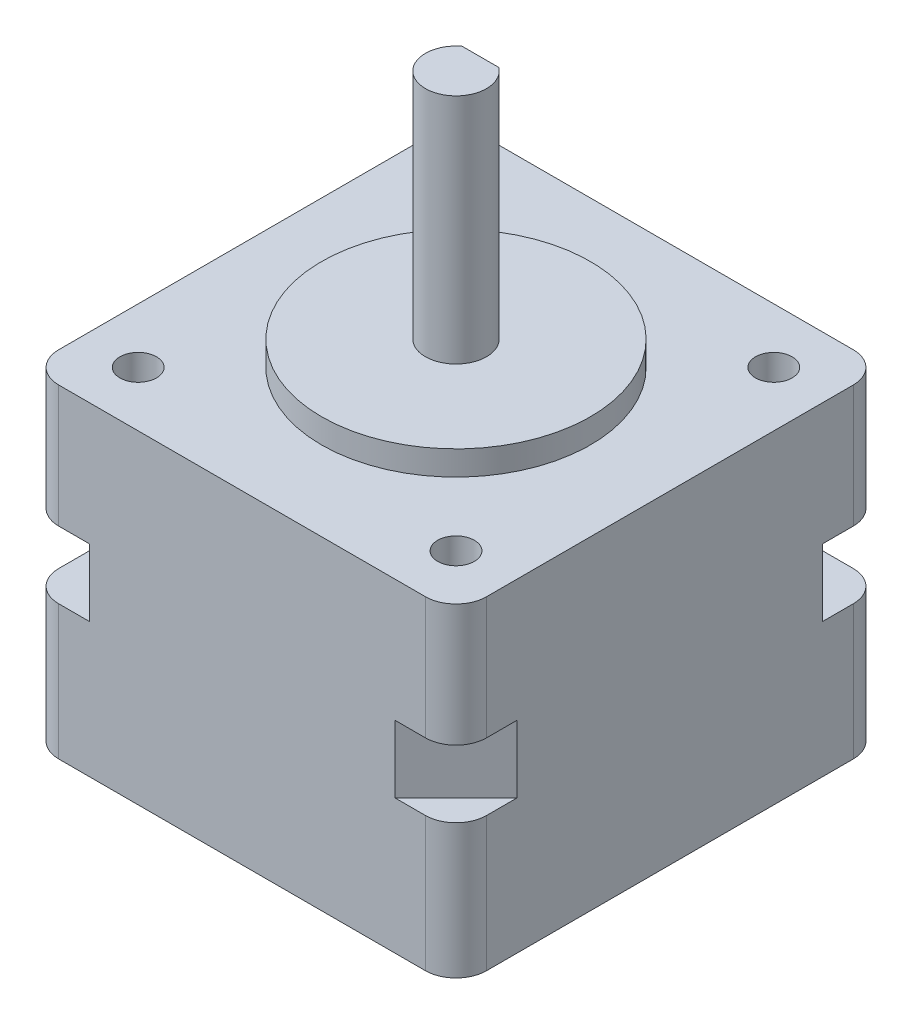
SolidWorks part; units mm, degrees
ref_plane "Plan de face" through (0, 0, 0) normal (0, 0, 1) x (1, 0, 0)
ref_plane "Plan de dessus" through (0, 0, 0) normal (0, 1, 0) x (1, 0, 0)
ref_plane "Plan de droite" through (0, 0, 0) normal (1, 0, 0) x (0, 0, -1)
sketch "Esquisse1" plane through (0, 0, 0) normal (0, 1, 0) x (1, 0, 0)
  line L1 (-17.5, 17.5) -> (17.5, 17.5)
  line L2 (-17.5, 17.5) -> (-17.5, -17.5)
  line L3 (-17.5, -17.5) -> (17.5, -17.5)
  line L4 (17.5, 17.5) -> (17.5, -17.5)
  point P4 (0, 17.5)
  point P6 (-17.5, 0)
  dimension "D1" = 35
extrude "Boss.-Extru.1" add sketch "Esquisse1" along normal blind 26.5
sketch "Esquisse2" plane through (0, 26.5, 0) normal (0, 1, 0) x (1, 0, 0)
  circle A0 centre (0, 0) radius 11
  dimension "D1" = 22
extrude "Boss.-Extru.2" add sketch "Esquisse2" along normal blind 2
sketch "Esquisse3" plane through (0, 28.5, 0) normal (0, 1, 0) x (1, 0, 0)
  line L0 (-1.5, 2) -> (1.5, 2)
  arc A1 (-1.5, 2) -> (1.5, 2) centre (0, 0) ccw
  point P5 (0, -2.5)
  dimension "D1" = 2.5
  dimension "D2" = 4.5
extrude "Boss.-Extru.3" add sketch "Esquisse3" along normal blind 19
hole_wizard "Diamètre du perçage Ø3.0 (3)1" positions "Esquisse7" profile "Esquisse6" hole size "Ø3.0" standard "DIN"
sketch "Esquisse7" plane through (0, 26.5, 0) normal (0, 1, 0) x (1, 0, 0)
  line L0 (0, 0) -> (0, 4.5387) construction
  line L2 (0, 0) -> (4.1956, 0) construction
  point P0 (-13, 13)
  point P12 (13, 13)
  point P13 (13, -13)
  point P14 (-13, -13)
  dimension "D1" = 26
  dimension "D2" = 26
sketch "Esquisse6" plane through (-13, 26.5, -13) normal (1, 0, 0) x (0, 0, 1)
  line L0 (0, 0) -> (0, 5.1013)
  line L1 (0, 5.1013) -> (1.5, 4.2)
  line L2 (1.5, 4.2) -> (1.5, 0)
  line L5 (1.5, 0) -> (0, 0)
  line L10 (0, 5.1013) -> (-1.5, 4.2) construction
  line L11 (0, -6.35) -> (0, 107.95) construction
  dimension "Diamètre du perçage" = 3
  dimension "Profondeur du perçage" = 4.2
  dimension "Angle de pointe" = 118
fillet "Congé1" radius 2.5 4 edges at (17.5, 13.25, -17.5) (-17.5, 13.25, -17.5) (17.5, 13.25, 17.5) (-17.5, 13.25, 17.5)
sketch "Esquisse4" plane through (0, 0, 0) normal (0, 1, 0) x (1, 0, 0)
  line L0 (0, 0) -> (0, 5.1071) construction
  line L1 (0, 0) -> (5.8035, 0) construction
  line L2 (-12.5, 17.5) -> (-17.5, 12.5)
  line L3 (15, 17.5) -> (-15, 17.5) construction
  line L4 (-17.5, 15) -> (-17.5, -15) construction
  line L5 (-17.5, 12.5) -> (-17.5, 17.5)
  line L6 (-17.5, 17.5) -> (-12.5, 17.5)
  line L7 (17.5, 17.5) -> (12.5, 17.5)
  line L8 (17.5, 12.5) -> (17.5, 17.5)
  line L9 (12.5, 17.5) -> (17.5, 12.5)
  line L10 (12.5, -17.5) -> (17.5, -12.5)
  line L11 (17.5, -12.5) -> (17.5, -17.5)
  line L12 (17.5, -17.5) -> (12.5, -17.5)
  line L13 (-17.5, -17.5) -> (-12.5, -17.5)
  line L14 (-17.5, -12.5) -> (-17.5, -17.5)
  line L15 (-12.5, -17.5) -> (-17.5, -12.5)
  dimension "D1" = 5
extrude "Enlèv. mat.-Extru.1" cut sketch "Esquisse4" along normal blind 5.5 from offset 11
sketch "Esquisse5" plane through (-17.5, 0, 0) normal (-1, 0, 0) x (0, 0, 1)
  line L0 (0, 0) -> (0, 2.0466) construction
  line L1 (-15, 0) -> (15, 0) construction
  circle A0 centre (-1, 7) radius 0.7
  circle A1 centre (-1, 5) radius 0.6547
  circle A2 centre (1, 5) radius 0.6547
  circle A3 centre (1, 7) radius 0.7
  dimension "D2" = 1.4
  dimension "D1" = 2
  dimension "D3" = 2
  dimension "D4" = 5
extrude "Boss.-Extru.4" add sketch "Esquisse5" along normal blind 10
equation "\"D3@Esquisse5\"=\"D1@Esquisse5\""
equation "\"D2@Esquisse7\"=\"D1@Esquisse7\""
